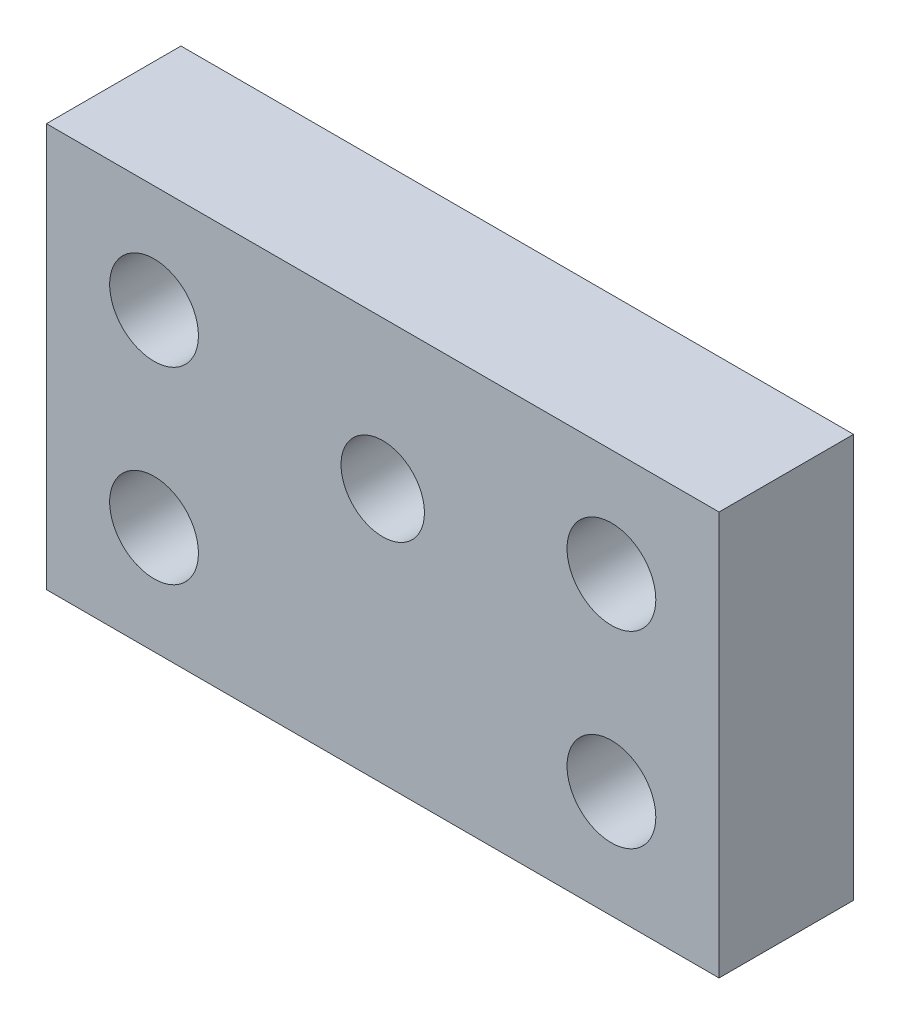
SolidWorks part; units mm, degrees
ref_plane "Płaszczyzna przednia" through (0, 0, 0) normal (0, 0, 1) x (1, 0, 0)
ref_plane "Płaszczyzna górna" through (0, 0, 0) normal (0, 1, 0) x (1, 0, 0)
ref_plane "Płaszczyzna prawa" through (0, 0, 0) normal (1, 0, 0) x (0, 0, -1)
sketch "Szkic1" plane through (0, 0, 0) normal (0, 0, 1) x (1, 0, 0)
  line L0 (0, 0) -> (0, 11.9041) construction
  line L1 (17, 9.8573) -> (17, -0.7465) construction
  line L2 (0, 7) -> (17, 0) construction
  line L3 (0, 0) -> (17, 7) construction
  line L5 (-4, 11) -> (21, 11)
  line L6 (-4, 11) -> (-4, -4)
  line L7 (-4, -4) -> (21, -4)
  line L8 (21, 11) -> (21, -4)
  line L9 (-4, 11) -> (21, -4) construction
  line L10 (-4, -4) -> (21, 11) construction
  circle A0 centre (0, 0) radius 1.65
  circle A1 centre (0, 7) radius 1.65
  circle A2 centre (17, 0) radius 1.65
  circle A3 centre (17, 7) radius 1.65
  point P12 (8.5, 3.5)
  dimension "D1" = 7
  dimension "D2" = 3.3
  dimension "D3" = 3.3
  dimension "D4" = 3.3
  dimension "D5" = 3.3
  dimension "D6" = 17
  dimension "D7" = 25
  dimension "D8" = 15
extrude "Dodanie-wyciągnięcie1" add sketch "Szkic1" along normal blind 5
sketch "Szkic2" plane through (0, 0, 5) normal (0, 0, 1) x (1, 0, 0)
  line L0 (0, 5.5) -> (22.5844, 5.5) construction
  line L1 (1.65, 7) -> (15.35, 7) construction
  line L2 (8.5, 7) -> (8.5, 0.9987) construction
  circle A0 centre (0, 7) radius 1.65 construction
  circle A1 centre (17, 7) radius 1.65 construction
  circle A2 centre (8.5, 5.5) radius 1.55
  dimension "D2" = 3.1
  dimension "D1" = 1.5
extrude "Wytnij-wyciągnięcie1" cut sketch "Szkic2" against normal blind 5
